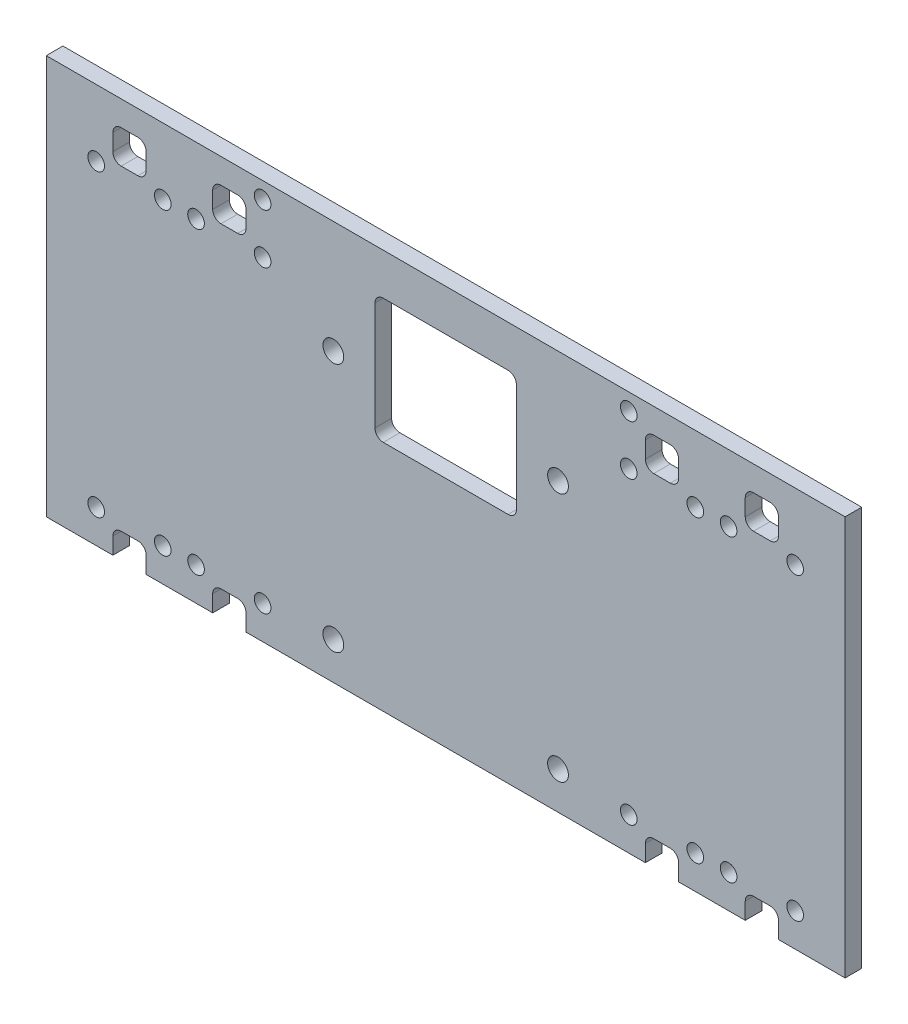
SolidWorks part; units mm, degrees
material "自訂玻璃纖維"
ref_plane "前基準面" through (0, 0, 0) normal (0, 0, 1) x (1, 0, 0)
ref_plane "上基準面" through (0, 0, 0) normal (0, 1, 0) x (1, 0, 0)
ref_plane "右基準面" through (0, 0, 0) normal (1, 0, 0) x (0, 0, -1)
sketch "草圖1" plane through (0, 0, 0) normal (0, 0, 1) x (1, 0, 0)
  line L0 (-53.6941, 36.9899) -> (-54.6941, 36.9899)
  line L1 (-53.6941, -11.0101) -> (-46.6941, -11.0101)
  line L2 (-54.6941, -10.0101) -> (-54.6941, 35.9899)
  line L3 (-53.6941, 36.9899) -> (40.3059, 36.9899)
  line L4 (41.3059, -10.0101) -> (41.3059, 35.9899)
  line L5 (-14.1941, 31.9899) -> (0.8059, 31.9899)
  line L6 (-15.1941, 30.9899) -> (-15.1941, 17.9899)
  line L7 (-14.1941, 16.9899) -> (0.8059, 16.9899)
  line L8 (1.8059, 30.9899) -> (1.8059, 17.9899)
  line L9 (-54.6941, 36.9899) -> (-54.6941, 35.9899)
  line L10 (-54.6941, -10.0101) -> (-54.6941, -11.0101)
  line L11 (-54.6941, -11.0101) -> (-53.6941, -11.0101)
  line L12 (40.3059, -11.0101) -> (41.3059, -11.0101)
  line L13 (41.3059, -11.0101) -> (41.3059, -10.0101)
  line L14 (40.3059, 36.9899) -> (41.3059, 36.9899)
  line L15 (41.3059, 36.9899) -> (41.3059, 35.9899)
  line L16 (-45.6941, -8.0101) -> (-43.6941, -8.0101)
  line L17 (-34.6941, -11.0101) -> (-34.6941, -9.0101)
  line L18 (-46.6941, -11.0101) -> (-46.6941, -9.0101)
  line L19 (-42.6941, -11.0101) -> (-34.6941, -11.0101)
  line L20 (-42.6941, -11.0101) -> (-42.6941, -9.0101)
  line L21 (-33.6941, -8.0101) -> (-31.6941, -8.0101)
  line L22 (-30.6941, -11.0101) -> (-30.6941, -9.0101)
  line L23 (17.3059, -11.0101) -> (17.3059, -9.0101)
  line L24 (18.3059, -8.0101) -> (20.3059, -8.0101)
  line L25 (21.3059, -11.0101) -> (21.3059, -9.0101)
  line L26 (29.3059, -11.0101) -> (29.3059, -9.0101)
  line L27 (30.3059, -8.0101) -> (32.3059, -8.0101)
  line L28 (33.3059, -11.0101) -> (33.3059, -9.0101)
  line L29 (21.3059, -11.0101) -> (29.3059, -11.0101)
  line L30 (33.3059, -11.0101) -> (40.3059, -11.0101)
  line L31 (-30.6941, -11.0101) -> (17.3059, -11.0101)
  line L32 (-46.6941, 30.9899) -> (-46.6941, 32.9899)
  line L33 (-45.6941, 33.9899) -> (-43.6941, 33.9899)
  line L34 (-42.6941, 30.9899) -> (-42.6941, 32.9899)
  line L35 (-45.6941, 29.9899) -> (-43.6941, 29.9899)
  line L36 (-30.6941, 30.9899) -> (-30.6941, 32.9899)
  line L37 (-34.6941, 30.9899) -> (-34.6941, 32.9899)
  line L38 (-33.6941, 29.9899) -> (-31.6941, 29.9899)
  line L39 (-33.6941, 33.9899) -> (-31.6941, 33.9899)
  line L41 (20.3059, 33.9899) -> (18.3059, 33.9899)
  line L42 (20.3059, 29.9899) -> (18.3059, 29.9899)
  line L43 (21.3059, 30.9899) -> (21.3059, 32.9899)
  line L44 (17.3059, 30.9899) -> (17.3059, 32.9899)
  line L45 (32.3059, 29.9899) -> (30.3059, 29.9899)
  line L46 (29.3059, 30.9899) -> (29.3059, 32.9899)
  line L47 (32.3059, 33.9899) -> (30.3059, 33.9899)
  line L48 (33.3059, 30.9899) -> (33.3059, 32.9899)
  circle A0 centre (-20.1941, 23.4899) radius 1.25
  circle A1 centre (6.8059, 23.4899) radius 1.25
  circle A2 centre (6.8059, -6.5101) radius 1.25
  circle A3 centre (-20.1941, -6.5101) radius 1.25
  circle A4 centre (27.3059, 28.9899) radius 1
  circle A5 centre (-48.6941, 28.9899) radius 1
  circle A6 centre (-28.6941, 34.9899) radius 1
  circle A7 centre (-36.6941, 28.9899) radius 1
  circle A8 centre (-28.6941, -7.0101) radius 1
  circle A9 centre (15.3059, 34.9899) radius 1
  circle A10 centre (-28.6941, 28.9899) radius 1
  circle A11 centre (-36.6941, -7.0101) radius 1
  arc A12 (-15.1941, 17.9899) -> (-14.1941, 16.9899) centre (-14.1941, 17.9899) ccw
  arc A13 (0.8059, 16.9899) -> (1.8059, 17.9899) centre (0.8059, 17.9899) ccw
  arc A14 (0.8059, 31.9899) -> (1.8059, 30.9899) centre (0.8059, 30.9899) cw
  arc A15 (-14.1941, 31.9899) -> (-15.1941, 30.9899) centre (-14.1941, 30.9899) ccw
  circle A16 centre (-40.6941, -7.0101) radius 1
  circle A17 centre (-48.6941, -7.0101) radius 1
  circle A18 centre (35.3059, -7.0101) radius 1
  circle A19 centre (-40.6941, 28.9899) radius 1
  circle A20 centre (27.3059, -7.0101) radius 1
  circle A21 centre (23.3059, -7.0101) radius 1
  circle A22 centre (15.3059, 28.9899) radius 1
  circle A23 centre (15.3059, -7.0101) radius 1
  circle A24 centre (23.3059, 28.9899) radius 1
  circle A25 centre (35.3059, 28.9899) radius 1
  arc A26 (-46.6941, -9.0101) -> (-45.6941, -8.0101) centre (-45.6941, -9.0101) cw
  arc A27 (-43.6941, -8.0101) -> (-42.6941, -9.0101) centre (-43.6941, -9.0101) cw
  arc A28 (-34.6941, -9.0101) -> (-33.6941, -8.0101) centre (-33.6941, -9.0101) cw
  arc A29 (-31.6941, -8.0101) -> (-30.6941, -9.0101) centre (-31.6941, -9.0101) cw
  arc A30 (17.3059, -9.0101) -> (18.3059, -8.0101) centre (18.3059, -9.0101) cw
  arc A31 (20.3059, -8.0101) -> (21.3059, -9.0101) centre (20.3059, -9.0101) cw
  arc A32 (29.3059, -9.0101) -> (30.3059, -8.0101) centre (30.3059, -9.0101) cw
  arc A33 (32.3059, -8.0101) -> (33.3059, -9.0101) centre (32.3059, -9.0101) cw
  arc A34 (-46.6941, 32.9899) -> (-45.6941, 33.9899) centre (-45.6941, 32.9899) cw
  arc A35 (-43.6941, 33.9899) -> (-42.6941, 32.9899) centre (-43.6941, 32.9899) cw
  arc A36 (-46.6941, 30.9899) -> (-45.6941, 29.9899) centre (-45.6941, 30.9899) ccw
  arc A37 (-43.6941, 29.9899) -> (-42.6941, 30.9899) centre (-43.6941, 30.9899) ccw
  arc A38 (-34.6941, 32.9899) -> (-33.6941, 33.9899) centre (-33.6941, 32.9899) cw
  arc A39 (-31.6941, 29.9899) -> (-30.6941, 30.9899) centre (-31.6941, 30.9899) ccw
  arc A40 (-34.6941, 30.9899) -> (-33.6941, 29.9899) centre (-33.6941, 30.9899) ccw
  arc A41 (-31.6941, 33.9899) -> (-30.6941, 32.9899) centre (-31.6941, 32.9899) cw
  arc A42 (18.3059, 33.9899) -> (17.3059, 32.9899) centre (18.3059, 32.9899) ccw
  arc A43 (21.3059, 30.9899) -> (20.3059, 29.9899) centre (20.3059, 30.9899) cw
  arc A44 (18.3059, 29.9899) -> (17.3059, 30.9899) centre (18.3059, 30.9899) cw
  arc A45 (21.3059, 32.9899) -> (20.3059, 33.9899) centre (20.3059, 32.9899) ccw
  arc A46 (30.3059, 29.9899) -> (29.3059, 30.9899) centre (30.3059, 30.9899) cw
  arc A47 (33.3059, 30.9899) -> (32.3059, 29.9899) centre (32.3059, 30.9899) cw
  arc A48 (30.3059, 33.9899) -> (29.3059, 32.9899) centre (30.3059, 32.9899) ccw
  arc A49 (33.3059, 32.9899) -> (32.3059, 33.9899) centre (32.3059, 32.9899) ccw
  point P9 (-38.6941, -7.0101)
  point P17 (-33.6941, 36.9899)
  point P18 (20.3059, 36.9899)
  point P23 (-54.6941, -11.0101)
  point P25 (41.3059, -11.0101)
  point P28 (-54.6941, -11.0101)
  point P39 (-15.1941, 16.9899)
  point P46 (-15.1941, 31.9899)
  point P78 (25.3059, -7.0101)
  point P111 (-34.6941, -10.0101)
  point P112 (17.3059, -10.0101)
  dimension "D3" = 2.5
  dimension "D6" = 30
  dimension "D12" = 27
  dimension "D4" = 2
  dimension "D20" = 2
  dimension "D21" = 2
  dimension "D22" = 2
  dimension "D23" = 8
  dimension "D24" = 2
  dimension "D25" = 36
  dimension "D26" = 36
  dimension "D8" = 13.5
  dimension "D9" = 4
  dimension "D10" = 13.5
  dimension "D11" = 4
  dimension "D19" = 1
  dimension "D13" = 2
  dimension "D14" = 2
  dimension "D29" = 2
  dimension "D30" = 8
  dimension "D31" = 8
  dimension "D1" = 27
  dimension "D2" = 30
  dimension "D5" = 48
  dimension "D7" = 96
  dimension "D15" = 5
  dimension "D16" = 5
  dimension "D17" = 5
  dimension "D18" = 15
  dimension "D27" = 8
  dimension "D28" = 36
  dimension "D32" = 2
  dimension "D33" = 8
  dimension "D34" = 2
  dimension "D35" = 8
extrude "填料-伸長3" add sketch "草圖1" along normal blind 2
